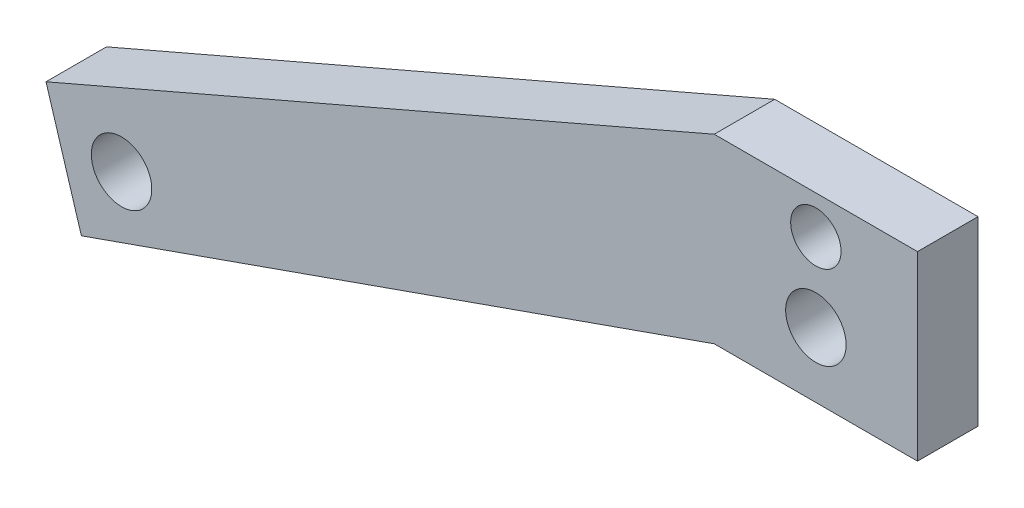
SolidWorks part; units mm, degrees
ref_plane "Front Plane" through (0, 0, 0) normal (0, 0, 1) x (1, 0, 0)
ref_plane "Top Plane" through (0, 0, 0) normal (0, 1, 0) x (1, 0, 0)
ref_plane "Right Plane" through (0, 0, 0) normal (1, 0, 0) x (0, 0, -1)
sketch "Sketch1" plane through (0, 0, 0) normal (0, 0, 1) x (1, 0, 0)
  line L0 (-16, 45) -> (-121.1993, -0.4465)
  line L2 (-276.7879, -13.7826) -> (-251.7788, -35.3348) construction
  line L3 (0, 26.6476) -> (-109.3056, -6.7705) construction
  line L4 (-16, 45) -> (-16, 15)
  line L5 (-16, 15) -> (16, 15)
  line L6 (16, 15) -> (16, 45)
  line L7 (16, 45) -> (-16, 45)
  line L8 (-16, 45) -> (-16, 16.425) construction
  line L9 (-16, 15) -> (16, 15) construction
  line L10 (16, 16.425) -> (16, 45)
  line L11 (16, 45) -> (-16, 45)
  line L12 (16, 16.425) -> (-16, 16.425)
  line L13 (-16, 16.425) -> (-115.6296, -18.6642)
  line L14 (-115.6296, -18.6642) -> (-121.1993, -0.4465)
  line L15 (-251.7788, -35.3348) -> (-242.2031, -37.4927) construction
  line L17 (-28.3991, 26.6361) -> (-28.037, 26.7) construction
  line L18 (-2117.156, -341.6) -> (-28.037, 26.7) construction
  line L19 (-242.2031, -37.4927) -> (-208.8903, -37.4927) construction
  line L20 (-208.8903, -37.4927) -> (-16, 45) construction
  line L21 (-292.5067, -43.5335) -> (-248.9466, -55.1606) construction
  line L22 (-248.9466, -55.1606) -> (-208.8903, -56.2396) construction
  line L23 (-208.8903, -56.2396) -> (-14.9476, 16.425) construction
  line L24 (-288.0555, -26.8574) -> (0, 26.6476) construction
  line L47 (-109.3056, -6.7705) -> (-118.4144, -9.5554) construction
  circle A0 centre (0, 39) radius 3.9688 construction
  circle A1 centre (0, 39) radius 3.9688
  circle A2 centre (0, 26.6476) radius 4.7625
  circle A3 centre (-109.3056, -6.7705) radius 4.7625
  circle A4 centre (-288.0555, -26.8574) radius 17.26 construction
  point P21 (-118.4144, -9.5554)
  dimension "D2" = 9.525
  dimension "D4" = 114.3
  dimension "D7" = 292.9825
  dimension "D3" = 9.525
  dimension "D5" = 19.05
  dimension "D6" = 28.575
  dimension "D8" = 17
  dimension "D9" = 32
  dimension "D1" = 0
extrude "Boss-Extrude1" add sketch "Sketch1" along normal blind 9.525
